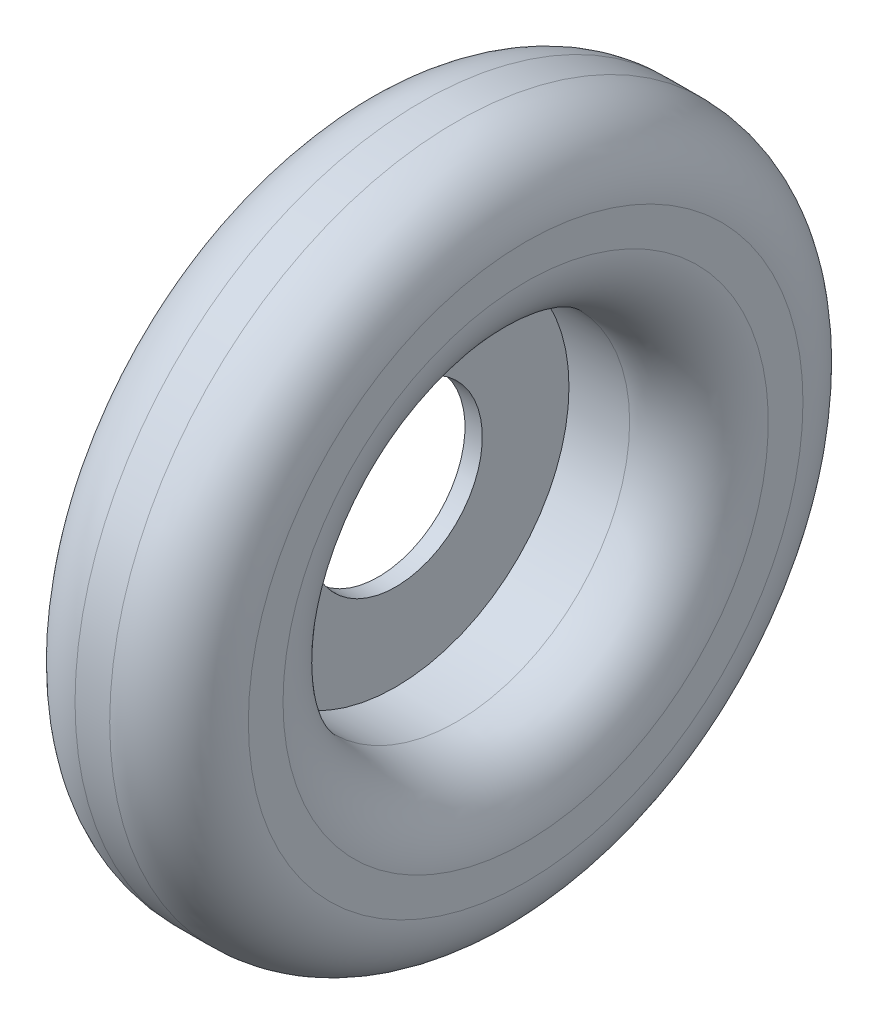
SolidWorks part; units mm, degrees
material "Rubber"
ref_plane "Front Plane" through (0, 0, 0) normal (0, 0, 1) x (1, 0, 0)
ref_plane "Top Plane" through (0, 0, 0) normal (0, 1, 0) x (1, 0, 0)
ref_plane "Right Plane" through (0, 0, 0) normal (1, 0, 0) x (0, 0, -1)
sketch "Sketch2" plane through (0, 0, 0) normal (0, 0, 1) x (1, 0, 0)
  line L0 (0, 50) -> (0, 100)
  line L1 (0, 50) -> (10, 50)
  line L2 (10, 100) -> (10, 50)
  line L3 (0, 0) -> (54.0274, 0) construction
  line L4 (25, 195) -> (45, 195)
  line L5 (-15, 160) -> (-15, 115)
  line L6 (25, 200) -> (45, 200)
  line L7 (85, 160) -> (85, 140)
  line L8 (45, 100) -> (10, 100)
  line L9 (-10, 160) -> (-10, 115)
  line L10 (80, 160) -> (80, 140)
  line L11 (45, 105) -> (0, 105)
  arc A0 (45, 200) -> (85, 160) centre (45, 160) cw
  arc A1 (-15, 160) -> (25, 200) centre (25, 160) cw
  arc A2 (85, 140) -> (45, 100) centre (45, 140) cw
  arc A3 (0, 100) -> (-15, 115) centre (0, 115) cw
  arc A4 (25, 195) -> (-10, 160) centre (25, 160) ccw
  arc A5 (80, 160) -> (45, 195) centre (45, 160) ccw
  arc A6 (45, 105) -> (80, 140) centre (45, 140) ccw
  arc A7 (-10, 115) -> (0, 105) centre (0, 115) ccw
  dimension "D7" = 40
  dimension "D8" = 40
  dimension "D1" = 10
  dimension "D2" = 50
  dimension "D4" = 100
  dimension "D6" = 50
  dimension "D10" = 35
revolve "Revolve1" add sketch "Sketch2" angle 360 about L3
